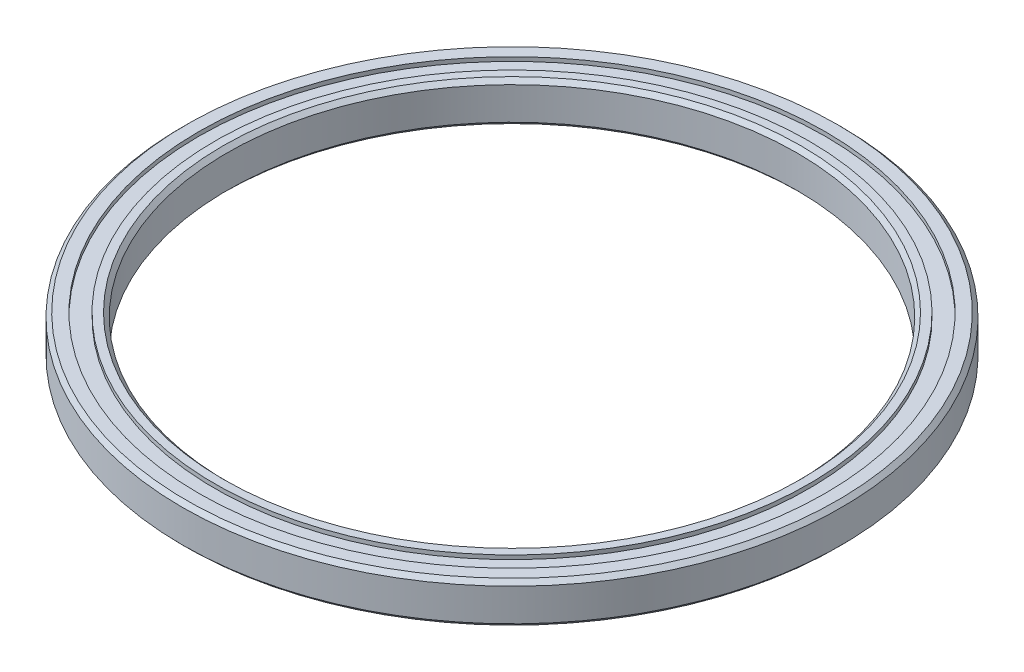
SolidWorks part; units mm, degrees
material "AISI 304"
ref_plane "前视基准面" through (0, 0, 0) normal (0, 0, 1) x (1, 0, 0)
ref_plane "上视基准面" through (0, 0, 0) normal (0, 1, 0) x (1, 0, 0)
ref_plane "右视基准面" through (0, 0, 0) normal (1, 0, 0) x (0, 0, -1)
sketch "草图1" plane through (0, 0, 0) normal (0, 0, 1) x (1, 0, 0)
  line L0 (0, 0) -> (0, 30) construction
  line L1 (-35.5, 0) -> (-36.5, 0)
  line L2 (-40.5, 0.5) -> (-40.5, 4.5)
  line L3 (-40, 5) -> (-38.5, 5)
  line L4 (-35, 4.5) -> (-35, 0.5)
  line L5 (-38.5, 5) -> (-38.5, 4.5)
  line L6 (-38.5, 4.5) -> (-36.5, 4.5)
  line L7 (-36.5, 4.5) -> (-36.5, 5)
  line L8 (-38.5, 0) -> (-38.5, 0.5)
  line L9 (-38.5, 0.5) -> (-36.5, 0.5)
  line L10 (-36.5, 0.5) -> (-36.5, 0)
  line L11 (-36.5, 5) -> (-35.5, 5)
  line L12 (-38.5, 0) -> (-40, 0)
  line L13 (-40.5, 4.5) -> (-40, 5)
  line L14 (-40, 0) -> (-40.5, 0.5)
  line L15 (-35.5, 5) -> (-35, 4.5)
  line L16 (-35, 0.5) -> (-35.5, 0)
  point P3 (-35, 0)
  point P4 (-40.5, 0)
  point P5 (-40.5, 5)
  point P7 (-35, 5)
  point P13 (-37.5, 0.5)
  dimension "D1" = 30
  dimension "D2" = 5
  dimension "D3" = 70
  dimension "D4" = 81
  dimension "D5" = 0.5
  dimension "D6" = 75
  dimension "D7" = 2
revolve "旋转1" add sketch "草图1" angle 360 about L0
